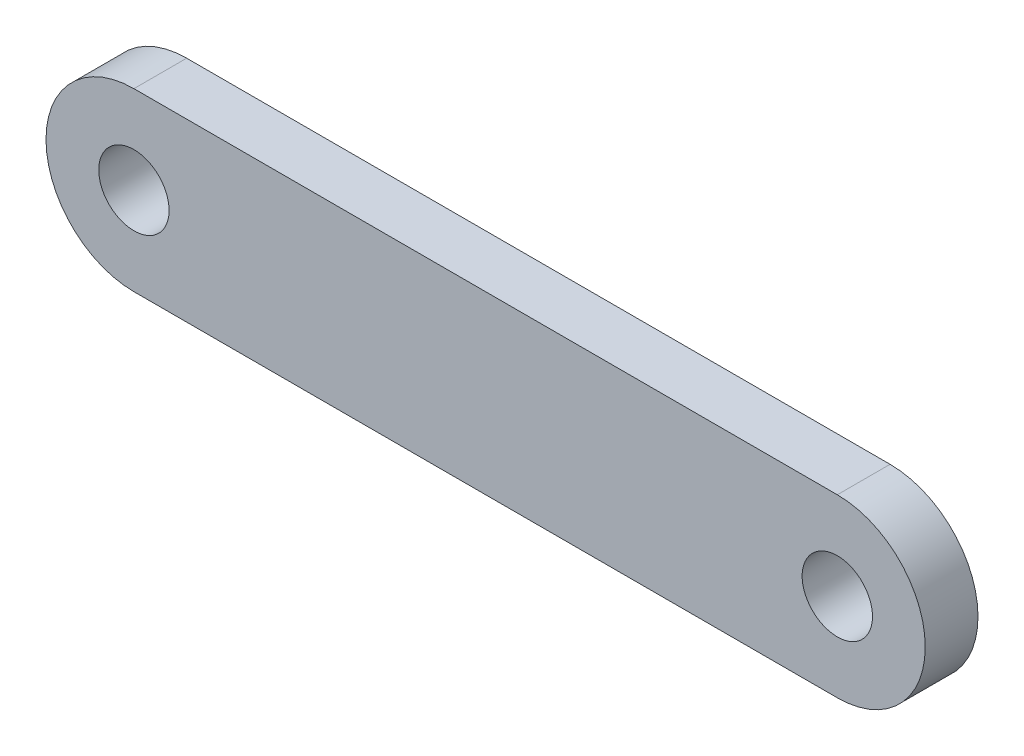
SolidWorks part; units mm, degrees
ref_plane "Plan de face" through (0, 0, 0) normal (0, 0, 1) x (1, 0, 0)
ref_plane "Plan de dessus" through (0, 0, 0) normal (0, 1, 0) x (1, 0, 0)
ref_plane "Plan de droite" through (0, 0, 0) normal (1, 0, 0) x (0, 0, -1)
sketch "Esquisse1" plane through (0, 0, 0) normal (0, 0, 1) x (1, 0, 0)
  line L0 (0, 0) -> (40, 0)
  line L1 (0, 10) -> (40, 10)
  arc A0 (0, 0) -> (0, 10) centre (0, 5) cw
  arc A1 (40, 10) -> (40, 0) centre (40, 5) cw
  circle A2 centre (0, 5) radius 2
  circle A3 centre (40, 5) radius 2
  dimension "D2" = 5
  dimension "D3" = 4
  dimension "D1" = 40
extrude "Boss.-Extru.1" add sketch "Esquisse1" along normal blind 3
